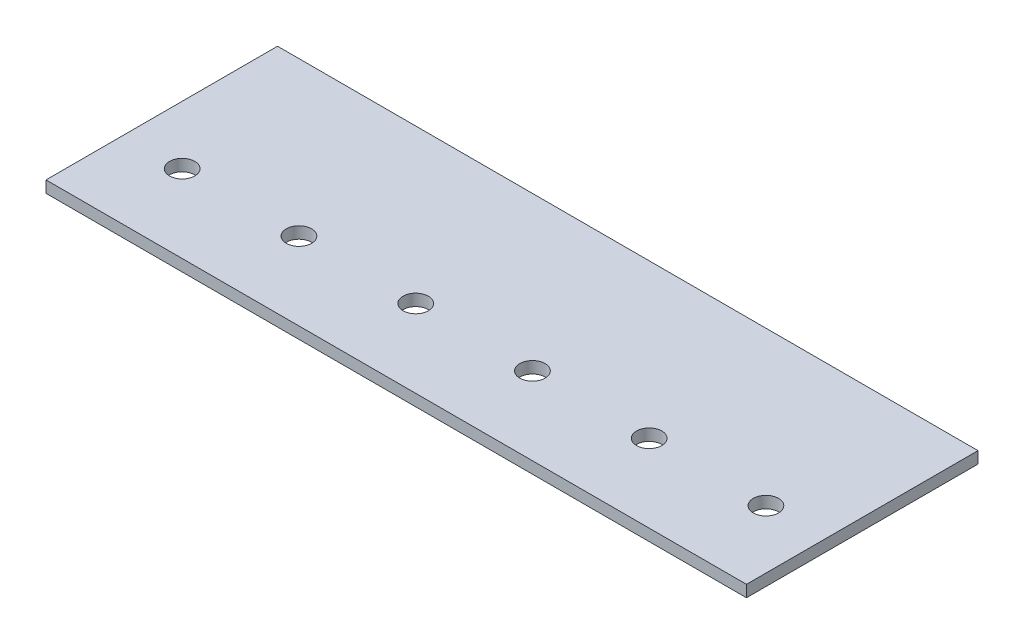
SolidWorks part; units mm, degrees
ref_plane "Ebene vorne" through (0, 0, 0) normal (0, 0, 1) x (1, 0, 0)
ref_plane "Ebene oben" through (0, 0, 0) normal (0, 1, 0) x (1, 0, 0)
ref_plane "Ebene rechts" through (0, 0, 0) normal (1, 0, 0) x (0, 0, -1)
sketch "Skizze1" plane through (0, 0, 0) normal (0, 1, 0) x (1, 0, 0)
  line L1 (-90, -29.75) -> (90, -29.75)
  line L2 (-90, -29.75) -> (-90, 29.75)
  line L3 (-90, 29.75) -> (90, 29.75)
  line L4 (90, -29.75) -> (90, 29.75)
  line L5 (-90, -29.75) -> (90, 29.75) construction
  line L6 (-90, 29.75) -> (90, -29.75) construction
  point P0 (0, 0)
  dimension "D1" = 180
  dimension "D2" = 59.5
extrude "Aufsatz-Linear austragen1" add sketch "Skizze1" along normal blind 3
sketch "Skizze2" plane through (0, 3, 0) normal (0, 1, 0) x (1, 0, 0)
  line L0 (-90, 29.75) -> (-90, -29.75) construction
  line L3 (-90, -29.75) -> (90, -29.75) construction
  line L4 (-90, 1.25) -> (90, 1.25)
  line L5 (90, -29.75) -> (90, 29.75) construction
  circle A0 centre (-75, -9.75) radius 3.25
  circle A1 centre (-45, -9.75) radius 3.25
  circle A2 centre (-15, -9.75) radius 3.25
  circle A3 centre (15, -9.75) radius 3.25
  circle A4 centre (45, -9.75) radius 3.25
  circle A5 centre (75, -9.75) radius 3.25
  dimension "D1" = 6.5
  dimension "D2" = 30
  dimension "D3" = 30
  dimension "D4" = 30
  dimension "D5" = 30
  dimension "D6" = 30
  dimension "D7" = 0
  dimension "D8" = 0
  dimension "D9" = 15
  dimension "D10" = 20
  dimension "D11" = 31
extrude "Schnitt-Linear austragen1" cut sketch "Skizze2" against normal blind 3 contours A0 | A1 | A2 | A3 | A4 | A5
sketch "Skizze3" plane through (0, 3, 0) normal (0, 1, 0) x (1, 0, 0)
  line L0 (-90, 1.25) -> (90, 1.25)
  line L1 (-90, 29.75) -> (-90, -29.75) construction
  line L2 (90, -29.75) -> (90, 29.75) construction
  dimension "D1" = 31
